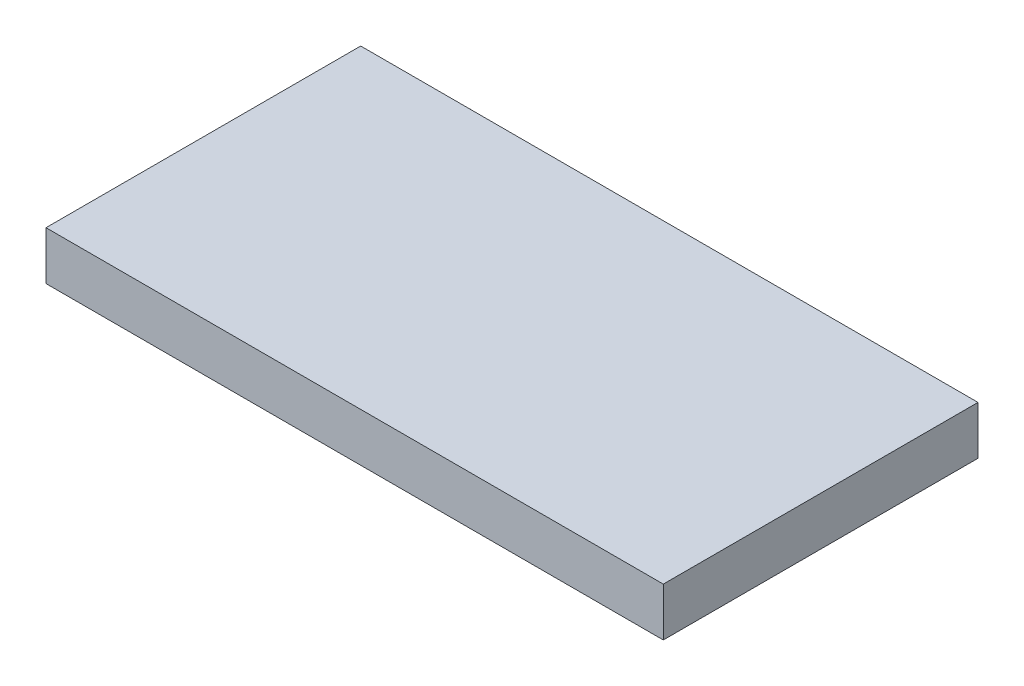
SolidWorks part; units mm, degrees
ref_plane "Спереди" through (0, 0, 0) normal (0, 0, 1) x (1, 0, 0)
ref_plane "Сверху" through (0, 0, 0) normal (0, 1, 0) x (1, 0, 0)
ref_plane "Справа" through (0, 0, 0) normal (1, 0, 0) x (0, 0, -1)
sketch "Эскиз1" plane through (0, 0, 0) normal (0, 1, 0) x (1, 0, 0)
  line L1 (0, 0) -> (51, 0)
  line L2 (0, 0) -> (0, 26)
  line L3 (0, 26) -> (51, 26)
  line L4 (51, 0) -> (51, 26)
  dimension "D1" = 51
  dimension "D2" = 26
extrude "Бобышка-Вытянуть1" add sketch "Эскиз1" along normal blind 4 contours L2 L3 L4 L1
